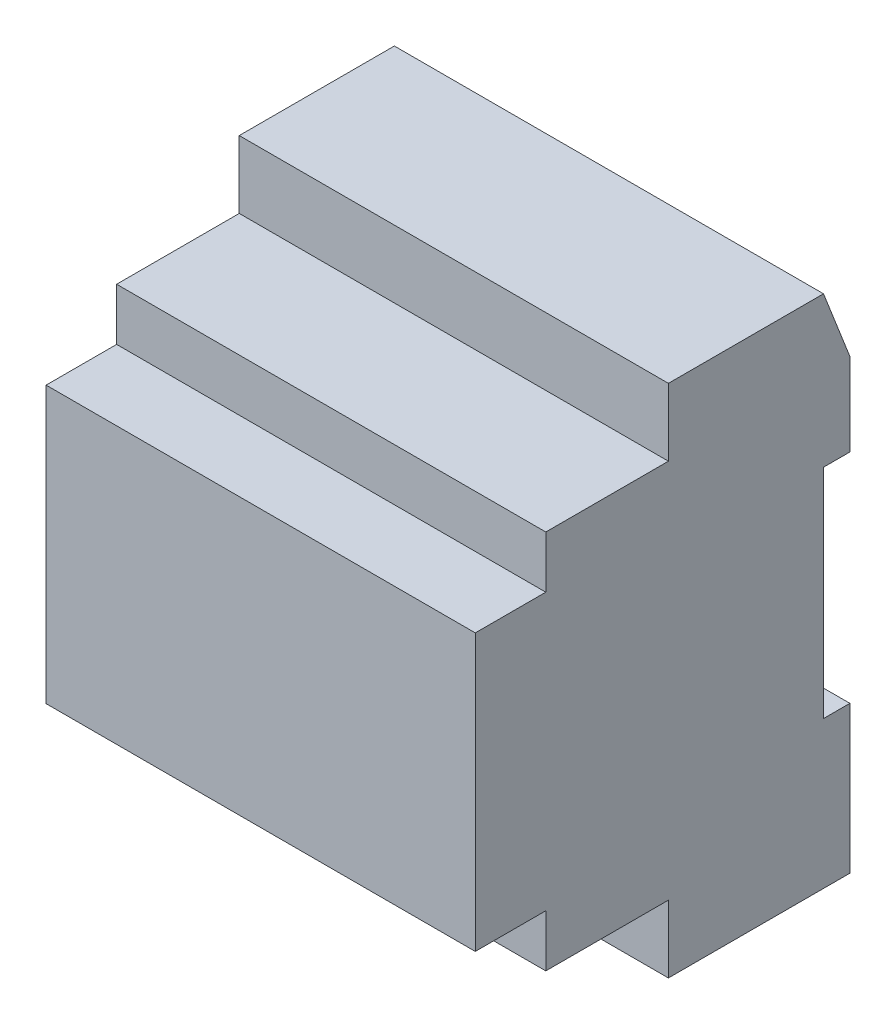
SolidWorks part; units mm, degrees
ref_plane "Piano frontale" through (0, 0, 0) normal (0, 0, 1) x (1, 0, 0)
ref_plane "Piano superiore" through (0, 0, 0) normal (0, 1, 0) x (1, 0, 0)
ref_plane "Piano destro" through (0, 0, 0) normal (1, 0, 0) x (0, 0, -1)
sketch "Schizzo1" plane through (0, 0, 0) normal (1, 0, 0) x (0, 0, -1)
  line L0 (-61.1, 64.5) -> (-61.1, 19.5)
  line L1 (-61.1, 19.5) -> (-49.6, 19.5)
  line L2 (-49.6, 19.5) -> (-49.6, 11)
  line L3 (-49.6, 11) -> (-29.6, 11)
  line L4 (-29.6, 11) -> (-29.6, 0)
  line L5 (-29.6, 0) -> (0, 0)
  line L6 (0, 0) -> (0, 24)
  line L7 (0, 24) -> (-4.3, 24)
  line L8 (-4.3, 24) -> (-4.3, 59.5)
  line L9 (-4.3, 59.5) -> (0, 59.5)
  line L10 (0, 59.5) -> (0, 73)
  line L11 (0, 73) -> (-4.3, 84)
  line L12 (-4.3, 84) -> (-29.6, 84)
  line L13 (-29.6, 84) -> (-29.6, 73)
  line L14 (-29.6, 73) -> (-49.6, 73)
  line L15 (-49.6, 73) -> (-49.6, 64.5)
  line L16 (-49.6, 64.5) -> (-61.1, 64.5)
  point P11 (0, 0)
  point P18 (0, 0)
  point P19 (0, 0)
  point P20 (0, 0)
  point P21 (-22.6876, 44.1183)
  point P22 (0, 0)
  point P23 (0, 0)
  point P24 (0, 0)
  dimension "D1" = 45
  dimension "D2" = 84
  dimension "D3" = 56.8
  dimension "D4" = 4.3
  dimension "D5" = 35.5
  dimension "D6" = 24.5
  dimension "D7" = 11
  dimension "D8" = 11
  dimension "D9" = 8.5
  dimension "D10" = 11.5
  dimension "D11" = 20
extrude "Estrusione-Estrusione1" add sketch "Schizzo1" along normal blind 70
sketch "Schizzo2" plane through (0, 0, 0) normal (0, -1, 0) x (1, 0, 0)
  line L0 (70, 0) -> (0, 0) construction
  line L1 (15, 0) -> (55, 0)
  line L2 (15, 0) -> (15, 4.3)
  line L3 (15, 4.3) -> (55, 4.3)
  line L4 (55, 0) -> (55, 4.3)
  line L5 (0, 29.6) -> (0, 0) construction
  dimension "D1" = 4.3
  dimension "D2" = 40
  dimension "D3" = 15
extrude "Estrusione-Estrusione2" add sketch "Schizzo2" along normal blind 4.8
